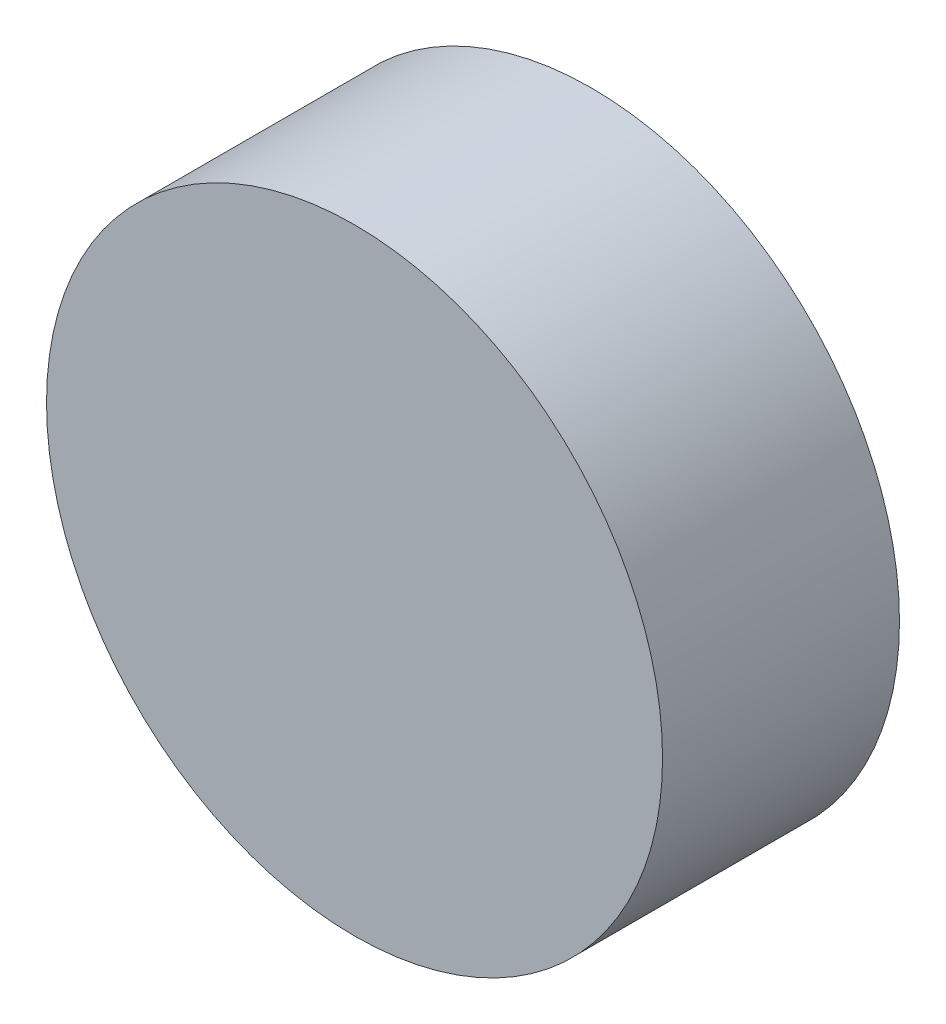
SolidWorks part; units mm, degrees
ref_plane "Plan de face" through (0, 0, 0) normal (0, 0, 1) x (1, 0, 0)
ref_plane "Plan de dessus" through (0, 0, 0) normal (0, 1, 0) x (1, 0, 0)
ref_plane "Plan de droite" through (0, 0, 0) normal (1, 0, 0) x (0, 0, -1)
sketch "Esquisse1" plane through (0, 0, 0) normal (0, 0, 1) x (1, 0, 0)
  circle A0 centre (0, 0) radius 13
  dimension "D1" = 26
extrude "Boss.-Extru.1" add sketch "Esquisse1" along normal blind 10
